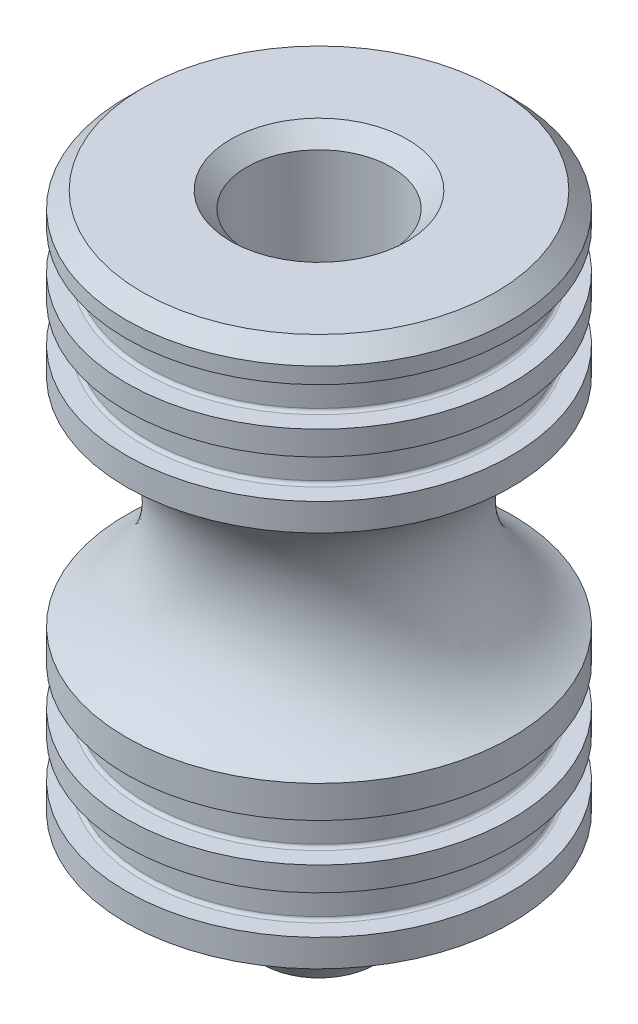
SolidWorks part; units mm, degrees
material "6061-T6 (SS)"
ref_plane "Piano frontale" through (0, 0, 0) normal (0, 0, 1) x (1, 0, 0)
ref_plane "Piano superiore" through (0, 0, 0) normal (0, 1, 0) x (1, 0, 0)
ref_plane "Piano destro" through (0, 0, 0) normal (1, 0, 0) x (0, 0, -1)
sketch "Schizzo1" plane through (0, 0, 0) normal (0, 0, 1) x (1, 0, 0)
  line L0 (0, 0) -> (0, 45.3488) construction
  line L1 (-12, 40) -> (-12, 30)
  line L2 (-12, 16.5) -> (-12, 6.5)
  line L3 (-12, 40) -> (-4.5, 40)
  line L4 (-4.5, 40) -> (-4.5, 18)
  line L5 (-4.5, 18) -> (0, 18)
  line L6 (0, 18) -> (0, 0)
  line L8 (0, 0) -> (-3.5, 0)
  line L9 (-12, 38) -> (-10.7, 38)
  line L10 (-10.7, 38) -> (-10.7, 35.6)
  line L11 (-10.7, 35.6) -> (-12, 35.6)
  line L12 (-12, 34.1) -> (-10.7, 34.1)
  line L13 (-10.7, 34.1) -> (-10.7, 31.7)
  line L14 (-10.7, 31.7) -> (-12, 31.7)
  line L15 (-12, 14.5) -> (-10.7, 14.5)
  line L16 (-10.7, 14.5) -> (-10.7, 12.1)
  line L17 (-10.7, 12.1) -> (-12, 12.1)
  line L18 (-12, 10.6) -> (-10.7, 10.6)
  line L19 (-10.7, 10.6) -> (-10.7, 8.2)
  line L20 (-10.7, 8.2) -> (-12, 8.2)
  arc A0 (-12, 16.5) -> (-12, 30) centre (-15.2692, 23.25) ccw
  arc A1 (-12, 6.5) -> (-3.5, 0) centre (-15.9948, -7.5317) cw
  dimension "D1" = 13.5
  dimension "D2" = 10
  dimension "D3" = 9
  dimension "D4" = 24
  dimension "D5" = 7
  dimension "D6" = 18
  dimension "D7" = 40
  dimension "D8" = 2.4
  dimension "D9" = 1.3
  dimension "D10" = 2
  dimension "D11" = 1.5
  dimension "D12" = 1.5
  dimension "D13" = 2
revolve "Rivoluzione2" add sketch "Schizzo1" angle 360 about L0
chamfer "Smusso1" distance 1 angle 45 2 edges at (0, 40, -4.5) (0, 40, -12)
hole_wizard "Foro filettato M8x1.0-1" positions "Schizzo2" profile "Schizzo3" tap size "M8x1.0" standard "ISO"
sketch "Schizzo2" plane through (0, 18, 0) normal (0, 1, 0) x (1, 0, 0)
  point P0 (0, 0)
sketch "Schizzo3" plane through (0, 18, 0) normal (1, 0, 0) x (0, 0, 1)
  line L0 (0, 0) -> (0, 9)
  line L1 (0, 9) -> (3.5, 6.897)
  line L2 (3.5, 6.897) -> (3.5, 0)
  line L5 (3.5, 0) -> (0, 0)
  line L10 (0, 9) -> (-3.5, 6.897) construction
  line L11 (0, -6.35) -> (0, 107.95) construction
  dimension "Tap Drill Dia." = 7
  dimension "Tap Drill Depth" = 9
  dimension "Drill Angle" = 118
cosmetic thread "Filettatura cosmetica1" parameters "D1"=6, "D2"=8
sketch "Schizzo6" plane through (0, 0, 0) normal (0, -1, 0) x (1, 0, 0)
  line L0 (-2, -1.1547) -> (-2, 1.1547)
  line L1 (-2, 1.1547) -> (0, 2.3094)
  line L2 (0, 2.3094) -> (2, 1.1547)
  line L3 (2, 1.1547) -> (2, -1.1547)
  line L4 (2, -1.1547) -> (0, -2.3094)
  line L5 (0, -2.3094) -> (-2, -1.1547)
  circle A0 centre (0, 0) radius 2.3094
  dimension "D1" = 4
extrude "Taglio-Estrusione1" cut sketch "Schizzo6" against normal blind 3 contours L5 L4 L3 L2 L1 L0
fillet "Raccordo1" radius 0.2 8 edges at (0, 14.5, -10.7) (0, 12.1, -10.7) (0, 10.6, -10.7) (0, 8.2, -10.7) (0, 34.1, -10.7) (0, 31.7, -10.7) (0, 38, -10.7) (0, 35.6, -10.7)
